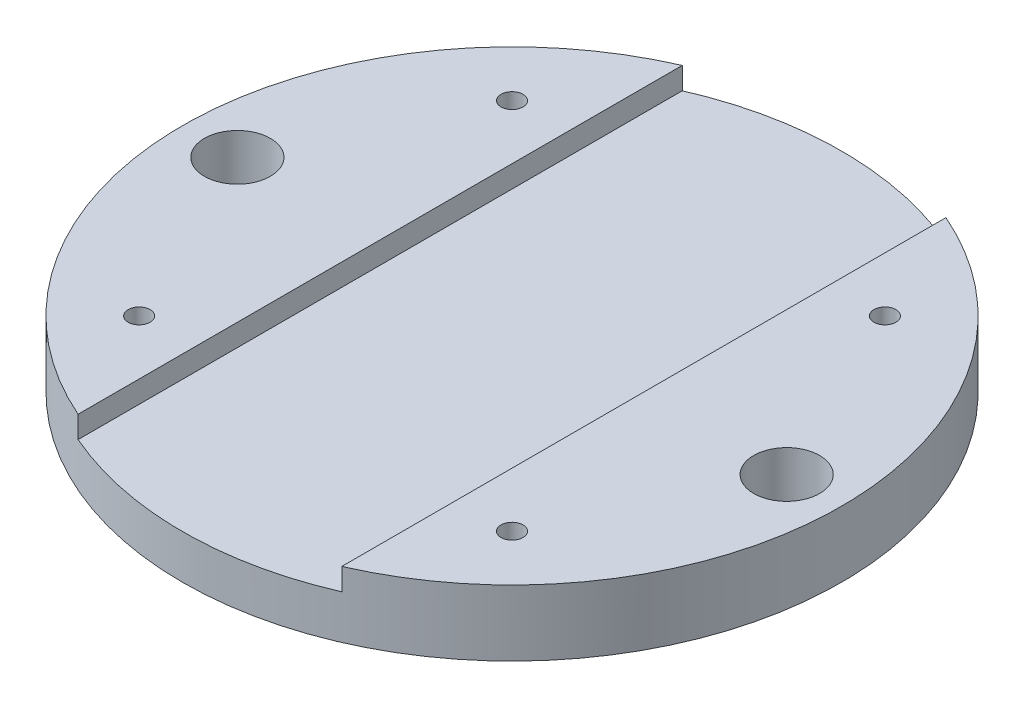
SolidWorks part; units mm, degrees
ref_plane "前视基准面" through (0, 0, 0) normal (0, 0, 1) x (1, 0, 0)
ref_plane "上视基准面" through (0, 0, 0) normal (0, 1, 0) x (1, 0, 0)
ref_plane "右视基准面" through (0, 0, 0) normal (1, 0, 0) x (0, 0, -1)
sketch "草图1" plane through (0, 0, 0) normal (0, 1, 0) x (1, 0, 0)
  circle A0 centre (0, 0) radius 15
  dimension "D1" = 30
extrude "凸台-拉伸1" add sketch "草图1" along normal blind 3
sketch "草图2" plane through (0, 0, 0) normal (0, 0, 1) x (1, 0, 0)
  line L0 (0, 10.5741) -> (0, 0) construction
  line L1 (0, 0) -> (0, -7.7516) construction
  line L2 (-6, 2) -> (6, 2)
  line L3 (6, 2) -> (6, 3)
  line L4 (15, 3) -> (-15, 3) construction
  line L5 (-6, 2) -> (-6, 3)
  point P11 (0, 2)
  dimension "D1" = 6
  dimension "D2" = 1
extrude "切除-拉伸2" cut sketch "草图2" against normal through all and the other way through all flip side to cut
sketch "草图3" plane through (0, 3, 0) normal (0, 1, 0) x (1, 0, 0)
  line L0 (0, 25.9857) -> (0, 0) construction
  line L1 (0, 0) -> (12.5, 0) construction
  line L2 (12.5, 0) -> (18.1107, 0) construction
  circle A0 centre (12.5, 0) radius 1.5
  circle A2 centre (-12.5, 0) radius 1.5
  dimension "D1" = 3
  dimension "D2" = 12.5
extrude "切除-拉伸3" cut sketch "草图3" against normal blind 3
sketch "草图4" plane through (0, 3, 0) normal (0, 1, 0) x (1, 0, 0)
  line L0 (-17.5714, 0) -> (0, 0) construction
  line L1 (0, 0) -> (18.3179, 0) construction
  line L2 (0, 16.222) -> (0, 0) construction
  line L3 (0, 0) -> (0, -16.7388) construction
  line L4 (0, 0) -> (13.0494, 13.0494) construction
  circle A0 centre (8.4853, 8.4853) radius 0.5
  circle A1 centre (-8.4853, 8.4853) radius 0.5
  circle A2 centre (8.4853, -8.4853) radius 0.5
  circle A3 centre (-8.4853, -8.4853) radius 0.5
  dimension "D1" = 1
  dimension "D2" = 12
  dimension "D3" = 45
extrude "切除-拉伸4" cut sketch "草图4" against normal blind 3
